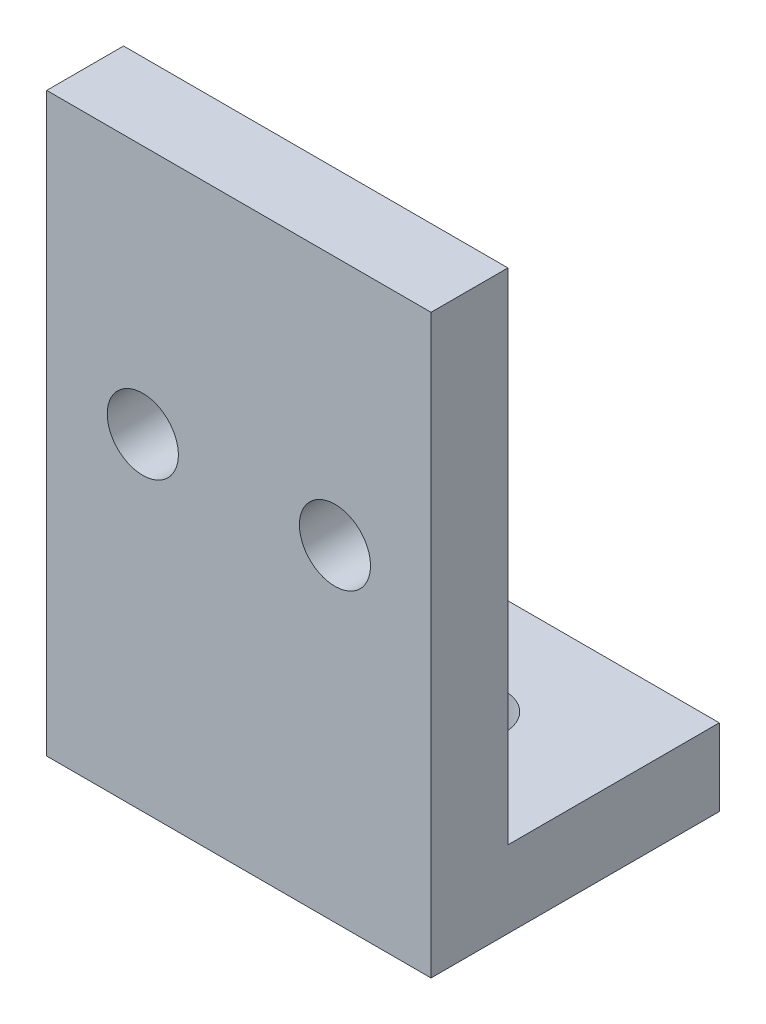
SolidWorks part; units mm, degrees
material "Onyx"
ref_plane "Front Plane" through (0, 0, 0) normal (0, 0, 1) x (1, 0, 0)
ref_plane "Top Plane" through (0, 0, 0) normal (0, 1, 0) x (1, 0, 0)
ref_plane "Right Plane" through (0, 0, 0) normal (1, 0, 0) x (0, 0, -1)
sketch "Sketch1" plane through (0, 0, 0) normal (1, 0, 0) x (0, 0, -1)
  line L0 (-4, 26) -> (0, 26)
  line L1 (0, 26) -> (0, 0)
  line L2 (0, 0) -> (11, 0)
  line L3 (11, 0) -> (11, -4)
  line L4 (11, -4) -> (-4, -4)
  line L5 (-4, -4) -> (-4, 26)
  dimension "D1" = 4
  dimension "D2" = 4
  dimension "D3" = 15
  dimension "D4" = 30
extrude "Boss-Extrude1" add sketch "Sketch1" along normal blind 10
sketch "Sketch2" plane through (0, 0, 0) normal (0, 1, 0) x (1, 0, 0)
  circle A0 centre (3, 5) radius 1.85
  circle A1 centre (3, 5) radius 1.7 construction
  dimension "D1" = 3.7
extrude "Cut-Extrude1" cut sketch "Sketch2" against normal through all
sketch "Sketch5" plane through (0, 0, 0) normal (-1, 0, 0) x (0, 0, 1)
  line L0 (4, -4) -> (-11, -4) construction
  line L1 (4, 26) -> (0, 26)
  line L2 (4, 26) -> (4, -4)
  line L3 (4, -4) -> (-11, -4)
  line L4 (-11, -4) -> (-11, 0)
  line L6 (-11, 0) -> (0, 0)
  line L7 (0, 0) -> (0, 26) construction
  line M2 (4, -4) -> (4, 26)
  line M3 (4, 26) -> (0, 26)
  line M4 (0, 26) -> (0, 0)
  line M5 (0, 0) -> (-11, 0)
  line M6 (-11, 0) -> (-11, -4)
  line M7 (-11, -4) -> (4, -4)
extrude "Boss-Extrude2" add sketch "Sketch5" along normal blind 10 contours M7 M2 M3 M4 M5 M6
sketch "Sketch4" plane through (0, 0, 0) normal (0, 0, -1) x (-1, 0, 0)
  line L0 (-10, 26) -> (0, 0) construction
  line L1 (0, 26) -> (-10, 0) construction
  line L2 (-10, 0) -> (10, 0) construction
  line L3 (-10, 26) -> (10, 26) construction
  line L4 (0, 26) -> (10, 0) construction
  line L5 (0, 0) -> (10, 26) construction
  circle A0 centre (-5, 13) radius 1.85
  circle A1 centre (5, 13) radius 1.85
  dimension "D1" = 3.7
extrude "Cut-Extrude2" cut sketch "Sketch4" against normal through all
chamfer "Chamfer1" distance 1 angle 45 2 edges at (3.15, 13, 0) (-6.85, 13, 0)
